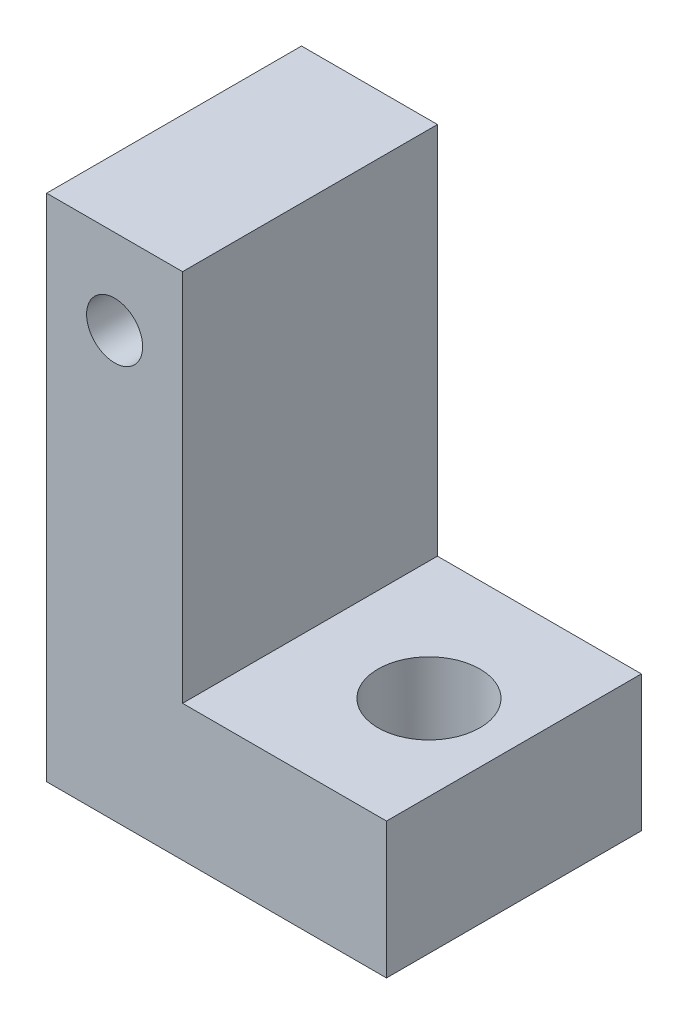
SolidWorks part; units mm, degrees
ref_plane "Piano frontale" through (0, 0, 0) normal (0, 0, 1) x (1, 0, 0)
ref_plane "Piano superiore" through (0, 0, 0) normal (0, 1, 0) x (1, 0, 0)
ref_plane "Piano destro" through (0, 0, 0) normal (1, 0, 0) x (0, 0, -1)
sketch "Schizzo1" plane through (0, 0, 0) normal (0, 0, 1) x (1, 0, 0)
  line L0 (0, 0) -> (-20, 0)
  line L1 (-20, 0) -> (-20, 30)
  line L2 (-20, 30) -> (-12, 30)
  line L3 (-12, 30) -> (-12, 8)
  line L4 (-12, 8) -> (0, 8)
  line L5 (0, 8) -> (0, 0)
  dimension "D1" = 20
  dimension "D2" = 12
  dimension "D3" = 30
  dimension "D4" = 8
extrude "Estrusione-Estrusione1" add sketch "Schizzo1" along normal blind 15
sketch "Schizzo2" plane through (0, 0, 0) normal (0, -1, 0) x (1, 0, 0)
  line L0 (0, 7.5) -> (-20, 7.5) construction
  line L1 (0, 15) -> (0, 0) construction
  line L2 (-20, 15) -> (-20, 0) construction
  circle A0 centre (-5, 7.5) radius 3
  dimension "D1" = 6
  dimension "D2" = 5
extrude "Taglio-Estrusione1" cut sketch "Schizzo2" against normal blind 15
sketch "Schizzo3" plane through (0, 0, 15) normal (0, 0, 1) x (1, 0, 0)
  line L0 (-16, 30) -> (-16, 0) construction
  line L1 (-12, 30) -> (-20, 30) construction
  line L2 (-20, 0) -> (0, 0) construction
  point P6 (-16, 25)
  dimension "D1" = 5
hole_wizard "Foro filettato M4-1" positions "Schizzo5" profile "Schizzo4" tap size "M4" standard "ISO" end condition through all
sketch "Schizzo5" plane through (0, 0, 15) normal (0, 0, 1) x (1, 0, 0)
  point P0 (-16, 25)
cosmetic thread "Filettatura del foro1" parameters "D2"=4
sketch "Schizzo4" plane through (-16, 25, 15) normal (1, 0, 0) x (0, -1, 0)
  line L0 (0, 0) -> (0, 15)
  line L1 (0, 15) -> (1.65, 15)
  line L2 (1.65, 15) -> (1.65, 0)
  line L5 (1.65, 0) -> (0, 0)
  line L11 (0, -6.35) -> (0, 107.95) construction
  dimension "Thru Tap Drill Dia." = 3.3
  dimension "Thru Tap Drill Depth" = 15
